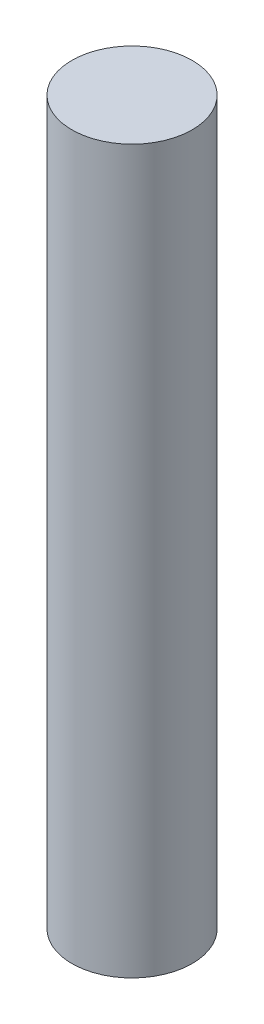
SolidWorks part; units mm, degrees
ref_plane "Front Plane" through (0, 0, 0) normal (0, 0, 1) x (1, 0, 0)
ref_plane "Top Plane" through (0, 0, 0) normal (0, 1, 0) x (1, 0, 0)
ref_plane "Right Plane" through (0, 0, 0) normal (1, 0, 0) x (0, 0, -1)
sketch "Sketch1" plane through (0, 0, 0) normal (0, 1, 0) x (1, 0, 0)
  circle A0 centre (0, 0) radius 6.35
  dimension "D1" = 12.7
extrude "Boss-Extrude1" add sketch "Sketch1" along normal mid plane 76.2
